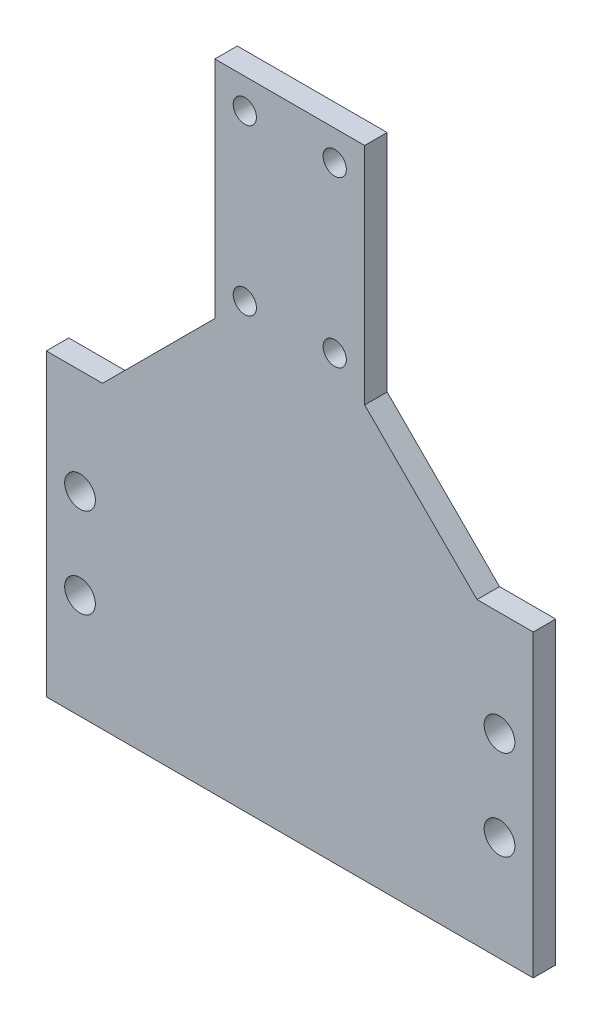
SolidWorks part; units mm, degrees
material "Thornel Mat VMA"
ref_plane "前视基准面" through (0, 0, 0) normal (0, 0, 1) x (1, 0, 0)
ref_plane "上视基准面" through (0, 0, 0) normal (0, 1, 0) x (1, 0, 0)
ref_plane "右视基准面" through (0, 0, 0) normal (1, 0, 0) x (0, 0, -1)
other "Configuration Table"
sketch "草图1" plane through (0, 0, 0) normal (0, 0, 1) x (1, 0, 0)
  line L0 (-32.5, 40) -> (-25, 40)
  line L1 (-25, 40) -> (-10, 55)
  line L2 (-10, 55) -> (-10, 85)
  line L3 (-10, 85) -> (10, 85)
  line L4 (-32.5, 40) -> (-32.5, 0)
  line L5 (-32.5, 0) -> (32.5, 0)
  line L6 (0, 0) -> (0, 50.9699) construction
  line L7 (32.5, 40) -> (32.5, 0)
  line L8 (10, 55) -> (10, 85)
  line L9 (25, 40) -> (10, 55)
  line L10 (32.5, 40) -> (25, 40)
  dimension "D1" = 65
  dimension "D2" = 85
  dimension "D3" = 30
  dimension "D4" = 40
  dimension "D5" = 50
  dimension "D6" = 20
extrude "凸台-拉伸1" add sketch "草图1" along normal blind 3
sketch "草图2" plane through (0, 0, 3) normal (0, 0, 1) x (1, 0, 0)
  line L0 (0, 85) -> (0, 65.679) construction
  line L1 (10, 85) -> (-10, 85) construction
  line L2 (-10, 70) -> (13.1812, 70) construction
  line L3 (-10, 85) -> (-10, 55) construction
  circle A0 centre (-6, 81) radius 1.55
  circle A2 centre (-6, 59) radius 1.55
  circle A3 centre (6, 59) radius 1.55
  circle A4 centre (6, 81) radius 1.55
  dimension "D1" = 4
  dimension "D2" = 4
  dimension "D3" = 3.1
extrude "切除-拉伸1" cut sketch "草图2" against normal through all
sketch "草图3" plane through (0, 0, 3) normal (0, 0, 1) x (1, 0, 0)
  line L0 (32.5, 20) -> (-48.6379, 20) construction
  line L1 (32.5, 0) -> (32.5, 40) construction
  line L2 (0, 0) -> (0, 100.1432) construction
  circle A0 centre (-28, 26) radius 2.05
  circle A2 centre (-28, 14) radius 2.05
  circle A3 centre (28, 14) radius 2.05
  circle A4 centre (28, 26) radius 2.05
  dimension "D1" = 12
  dimension "D2" = 56
  dimension "D3" = 4.1
extrude "切除-拉伸2" cut sketch "草图3" against normal through all
